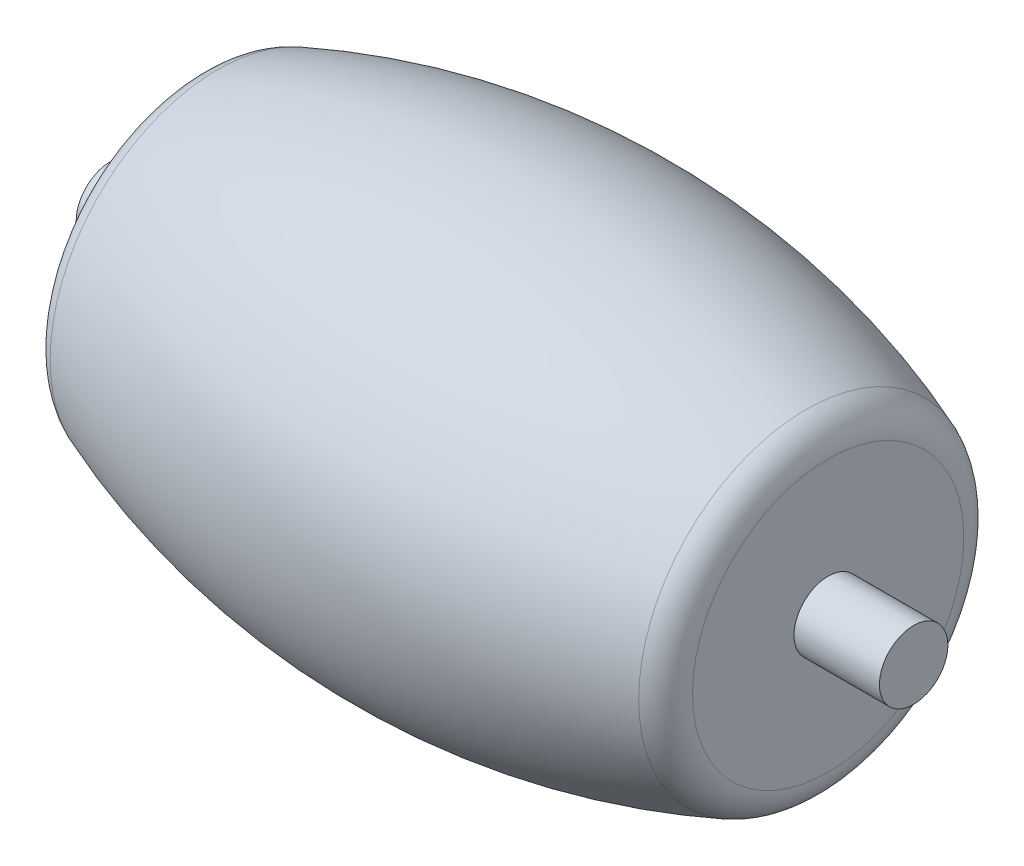
SolidWorks part; units mm, degrees
material "Полиуретан (11671)"
ref_plane "Спереди" through (0, 0, 0) normal (0, 0, 1) x (1, 0, 0)
ref_plane "Сверху" through (0, 0, 0) normal (0, 1, 0) x (1, 0, 0)
ref_plane "Справа" through (0, 0, 0) normal (1, 0, 0) x (0, 0, -1)
sketch "Эскиз1" plane through (0, 0, 0) normal (0, 0, 1) x (1, 0, 0)
  line L0 (0, 24) -> (0, 11) construction
  line L1 (-9.25, 22.1458) -> (-9.25, 17.5)
  line L2 (9.25, 22.1458) -> (9.25, 17.5)
  line L3 (-9.25, 17.5) -> (9.25, 17.5)
  line L4 (-9.25, 17.5) -> (13.2463, 17.5) construction
  arc A0 (9.25, 22.1458) -> (-9.25, 22.1458) centre (0, 0) ccw
  point P15 (0, 17.5)
revolve "Повернуть1" add sketch "Эскиз1" angle 360 about L4
sketch "Эскиз2" plane through (-9.25, 0, 0) normal (-1, 0, 0) x (0, 0, 1)
  circle A4 centre (0, 17.5) radius 0.75
  dimension "D1" = 1.5
extrude "Вырез-Вытянуть1" cut sketch "Эскиз2" against normal through all
fillet "Скругление1" radius 1 2 edges at (-9.25, 17.5, 4.6458) (9.25, 17.5, 4.6458)
sketch "Эскиз3" plane through (0, 0, 0) normal (1, 0, 0) x (0, 0, -1)
  circle A0 centre (0, 17.5) radius 0.75
  dimension "D1" = 1.5
ref_plane "Плоскость1" through (0, 0, 0) normal (-1, 0, 0) x (0, 0, 1)
sketch "Эскиз4" plane through (0, 0, 0) normal (-1, 0, 0) x (0, 0, 1)
  circle A0 centre (0, 17.5) radius 1
  dimension "D1" = 2
extrude "Бобышка-Вытянуть2" add sketch "Эскиз4" along normal blind 11.75 and the other way blind 11.75
